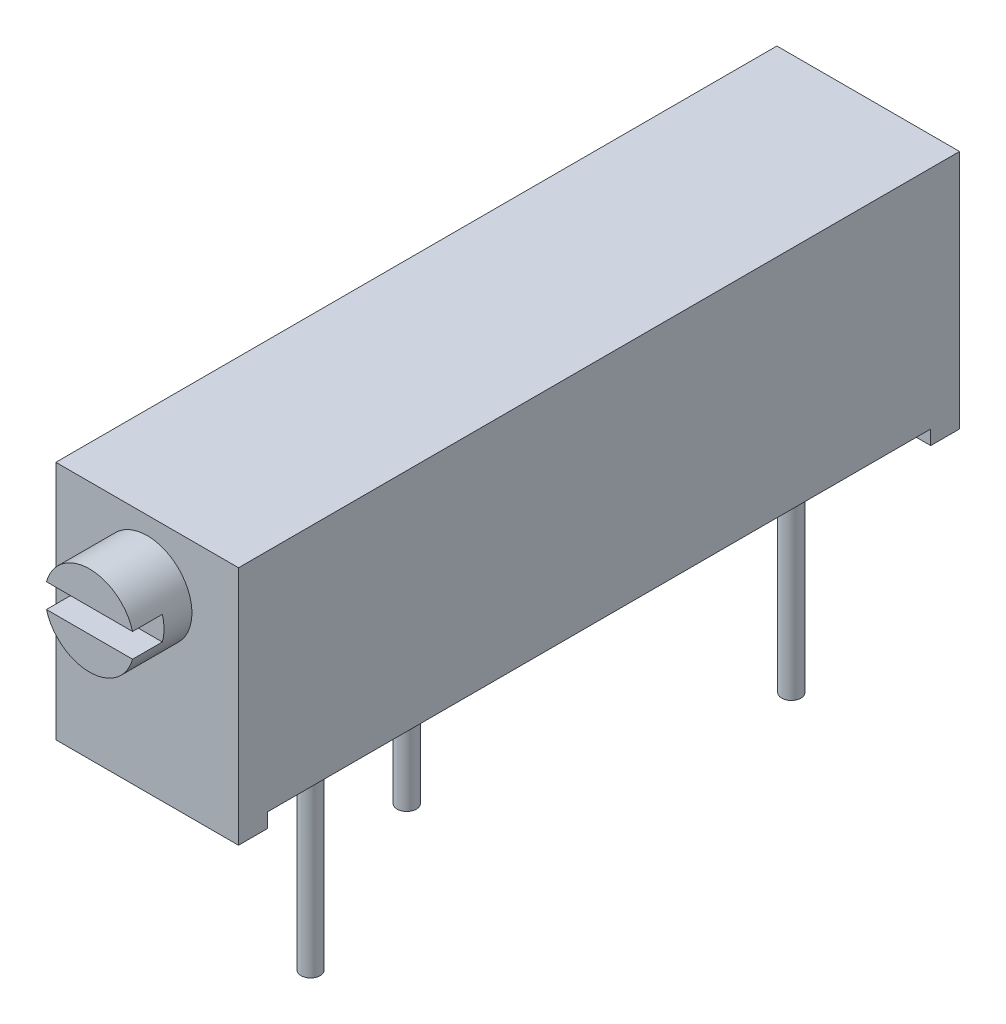
SolidWorks part; units mm, degrees
ref_plane "Front" through (0, 0, 0) normal (0, 0, 1) x (1, 0, 0)
ref_plane "Top" through (0, 0, 0) normal (0, 1, 0) x (1, 0, 0)
ref_plane "Right" through (0, 0, 0) normal (1, 0, 0) x (0, 0, -1)
sketch "Sketch1" plane through (0, 0, 0) normal (1, 0, 0) x (0, 0, -1)
  line L0 (-9.525, 0) -> (0, 0) construction
  line L1 (-9.525, 3.175) -> (9.525, 3.175)
  line L2 (-9.525, 3.175) -> (-9.525, -3.175)
  line L3 (-9.525, -3.175) -> (-8.763, -3.175)
  line L4 (9.525, 3.175) -> (9.525, -3.175)
  line L5 (0, 0) -> (0, 3.175) construction
  line L6 (-8.763, -2.794) -> (8.763, -2.794)
  line L7 (-8.763, -2.794) -> (-8.763, -3.175)
  line L8 (8.763, -2.794) -> (8.763, -3.175)
  line L9 (8.763, -3.175) -> (9.525, -3.175)
  dimension "D1" = 19.05
  dimension "D2" = 6.35
  dimension "D3" = 0.762
  dimension "D4" = 0.381
extrude "Extrude1" add sketch "Sketch1" along normal mid plane 4.826
sketch "Sketch2" plane through (0, 0, 9.525) normal (0, 0, 1) x (1, 0, 0)
  line L0 (2.413, -3.175) -> (-2.413, -3.175) construction
  circle A0 centre (0, 1.524) radius 1.1811
  dimension "D1" = 2.3622
  dimension "D2" = 4.699
extrude "Extrude2" add sketch "Sketch2" along normal blind 1.524
sketch "Sketch3" plane through (0, 0, 11.049) normal (0, 0, 1) x (1, 0, 0)
  line L0 (0, 1.524) -> (-2.413, 1.524) construction
  line L1 (-1.558, 1.8415) -> (1.546, 1.8415)
  line L2 (-1.558, 1.8415) -> (-1.558, 1.2065)
  line L4 (1.546, 1.8415) -> (1.546, 1.2065)
  line L5 (-2.413, 3.175) -> (-2.413, -3.175) construction
  line L6 (-1.558, 1.2065) -> (1.546, 1.2065)
  dimension "D1" = 0.3175
extrude "Cut-Extrude1" cut sketch "Sketch3" against normal blind 0.7874
sketch "Sketch4" plane through (0, -2.794, 0) normal (0, -1, 0) x (1, 0, 0)
  line L0 (2.413, 8.763) -> (2.413, -8.763) construction
  line L1 (2.413, 9.525) -> (-2.413, 9.525) construction
  circle A0 centre (1.016, 6.223) radius 0.254
  circle A1 centre (-1.524, 1.143) radius 0.254
  circle A2 centre (1.016, -6.477) radius 0.254
  dimension "D1" = 0.508
  dimension "D4" = 12.7
  dimension "D5" = 2.54
  dimension "D2" = 1.397
  dimension "D3" = 3.302
  dimension "D6" = 5.08
extrude "Extrude3" add sketch "Sketch4" along normal blind 5.588
